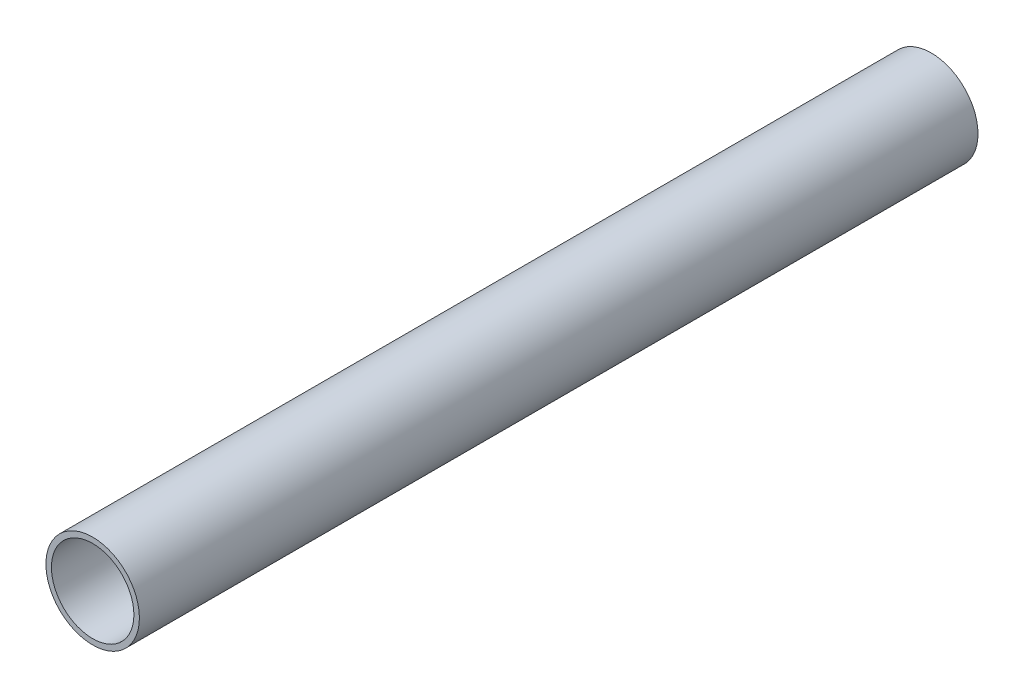
SolidWorks part; units mm, degrees
material "AISI 1010 钢，热轧条材"
ref_plane "前视基准面" through (0, 0, 0) normal (0, 0, 1) x (1, 0, 0)
ref_plane "上视基准面" through (0, 0, 0) normal (0, 1, 0) x (1, 0, 0)
ref_plane "右视基准面" through (0, 0, 0) normal (1, 0, 0) x (0, 0, -1)
sketch "草图1" plane through (0, 0, 0) normal (0, 0, 1) x (1, 0, 0)
  circle A0 centre (0, 0) radius 17
  circle A1 centre (0, 0) radius 15
  dimension "D1" = 34
  dimension "D2" = 2
extrude "凸台-拉伸1" add sketch "草图1" along normal blind 305
